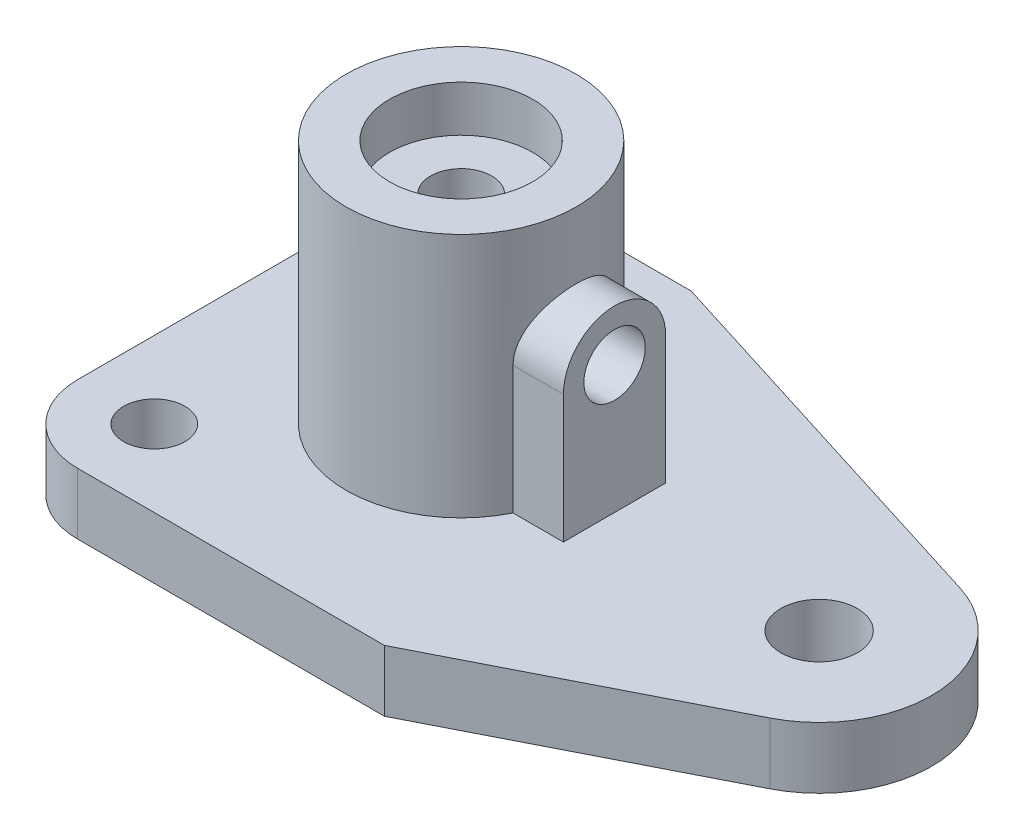
SolidWorks part; units mm, degrees
ref_plane "Front Plane" through (0, 0, 0) normal (0, 0, 1) x (1, 0, 0)
ref_plane "Top Plane" through (0, 0, 0) normal (0, 1, 0) x (1, 0, 0)
ref_plane "Right Plane" through (0, 0, 0) normal (1, 0, 0) x (0, 0, -1)
sketch "Sketch1" plane through (0, 0, 0) normal (0, 1, 0) x (1, 0, 0)
  line L0 (0, 0) -> (70, 0) construction
  line L1 (-45, 30) -> (-45, -30)
  line L2 (-30, 45) -> (0, 45)
  line L3 (0, 45) -> (76.581, 20.9926)
  line L4 (-30, -45) -> (30, -45)
  line L5 (30, -45) -> (79.9653, -19.6136)
  arc A0 (-30, 45) -> (-45, 30) centre (-30, 30) ccw
  arc A1 (-45, -30) -> (-30, -45) centre (-30, -30) ccw
  arc A2 (79.9653, -19.6136) -> (76.581, 20.9926) centre (70, 0) ccw
  circle A3 centre (-30, 30) radius 6
  circle A4 centre (-30, -30) radius 6
  circle A5 centre (70, 0) radius 7.5
  dimension "D1" = 30
  dimension "D2" = 44
  dimension "D8" = 12
  dimension "D9" = 15
  dimension "D3" = 60
  dimension "D4" = 30
  dimension "D5" = 100
  dimension "D6" = 30
  dimension "D7" = 60
extrude "Boss-Extrude1" add sketch "Sketch1" along normal blind 12
sketch "Sketch2" plane through (0, 12, 0) normal (0, 1, 0) x (1, 0, 0)
  circle A0 centre (0, 0) radius 22.5
  dimension "D1" = 45
extrude "Boss-Extrude2" add sketch "Sketch2" along normal blind 48
hole_wizard "Hole1" positions "Sketch3" profile "Sketch4" legacy
sketch "Sketch3" plane through (0, 60, 0) normal (0, 1, 0) x (1, 0, 0)
  point P0 (0, 0)
sketch "Sketch4" plane through (0, 60, 0) normal (1, 0, 0) x (0, 0, 1)
  line L0 (0, 0) -> (0, 100)
  line L1 (0, 100) -> (6, 100)
  line L2 (6, 100) -> (6, 9)
  line L3 (6, 9) -> (14, 9)
  line L4 (14, 9) -> (14, 0)
  line L5 (14, 0) -> (0, 0)
  line L6 (0, 110) -> (0, -10) construction
  dimension "Diameter" = 12
  dimension "Depth" = 100
  dimension "C-Bore Diameter" = 28
  dimension "C-Bore Depth" = 9
sketch "Sketch5" plane through (0, 0, 0) normal (1, 0, 0) x (0, 0, -1)
  line L2 (-10, 37) -> (-10, 0)
  line L4 (10, 0) -> (10, 37)
  line L5 (0, 0) -> (0, 14.238) construction
  line L6 (-10, 0) -> (10, 0)
  line L7 (-19.6136, 0) -> (20.9926, 0) construction
  arc A0 (10, 37) -> (-10, 37) centre (0, 37) ccw
  dimension "D1" = 20
  dimension "D2" = 37
extrude "Boss-Extrude5" add sketch "Sketch5" along normal blind 15 from offset 15
hole_wizard "Hole2" positions "Sketch6" profile "Sketch7" legacy
sketch "Sketch6" plane through (30, 0, 0) normal (1, 0, 0) x (0, 0, -1)
  point P0 (0, 37)
sketch "Sketch7" plane through (30, 37, 0) normal (0, 1, 0) x (0, 0, -1)
  line L0 (0, 0) -> (0, 24)
  line L1 (0, 24) -> (6, 24)
  line L2 (6, 24) -> (6, 0)
  line L3 (6, 0) -> (0, 0)
  line L4 (0, 110) -> (0, -10) construction
  dimension "Diameter" = 12
  dimension "Depth" = 24
